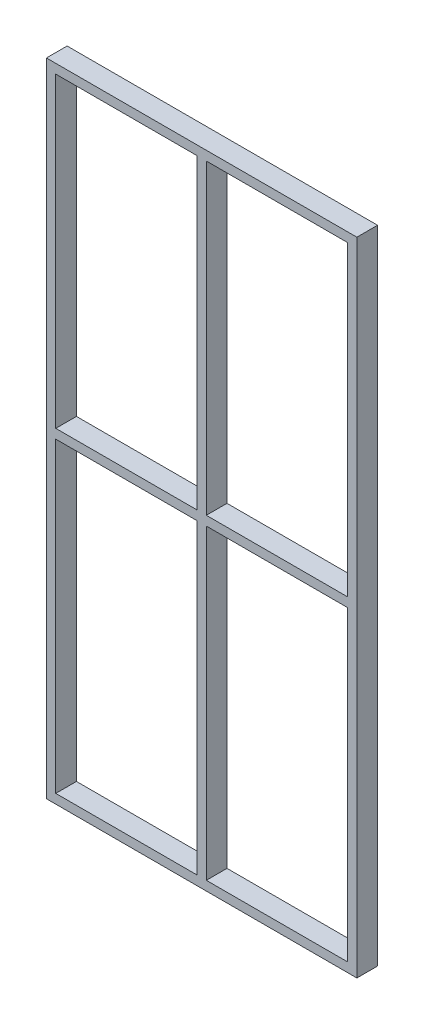
SolidWorks part; units mm, degrees
ref_plane "Plan de face" through (0, 0, 0) normal (0, 0, 1) x (1, 0, 0)
ref_plane "Plan de dessus" through (0, 0, 0) normal (0, 1, 0) x (1, 0, 0)
ref_plane "Plan de droite" through (0, 0, 0) normal (1, 0, 0) x (0, 0, -1)
sketch "Esquisse1" plane through (0, 0, 0) normal (0, 0, 1) x (1, 0, 0)
  line L0 (0, 0) -> (900, 0)
  line L1 (900, 0) -> (900, 1860)
  line L2 (900, 1860) -> (0, 1860)
  line L3 (0, 1860) -> (0, 0)
  dimension "D1" = 900
  dimension "D2" = 1860
extrude "Extru.-Mince1" add sketch "Esquisse1" along normal blind 60 thin thin type one direction reverse wall 27
sketch "Esquisse2" plane through (0, 0, 60) normal (0, 0, 1) x (1, 0, 0)
  line L0 (450, 27) -> (450, 1833)
  line L1 (27, 27) -> (873, 27) construction
  line L2 (873, 1833) -> (27, 1833) construction
extrude "Extru.-Mince2" add sketch "Esquisse2" against normal blind 60 thin thin type mid plane wall 27
sketch "Esquisse3" plane through (0, 0, 60) normal (0, 0, 1) x (1, 0, 0)
  line L0 (27, 930) -> (873, 930)
  line L1 (27, 1833) -> (27, 27) construction
  line L2 (873, 27) -> (873, 1833) construction
extrude "Extru.-Mince3" add sketch "Esquisse3" against normal up to vertex (60 mm away) thin up to point (27, 27, 0) thin type mid plane wall 27
